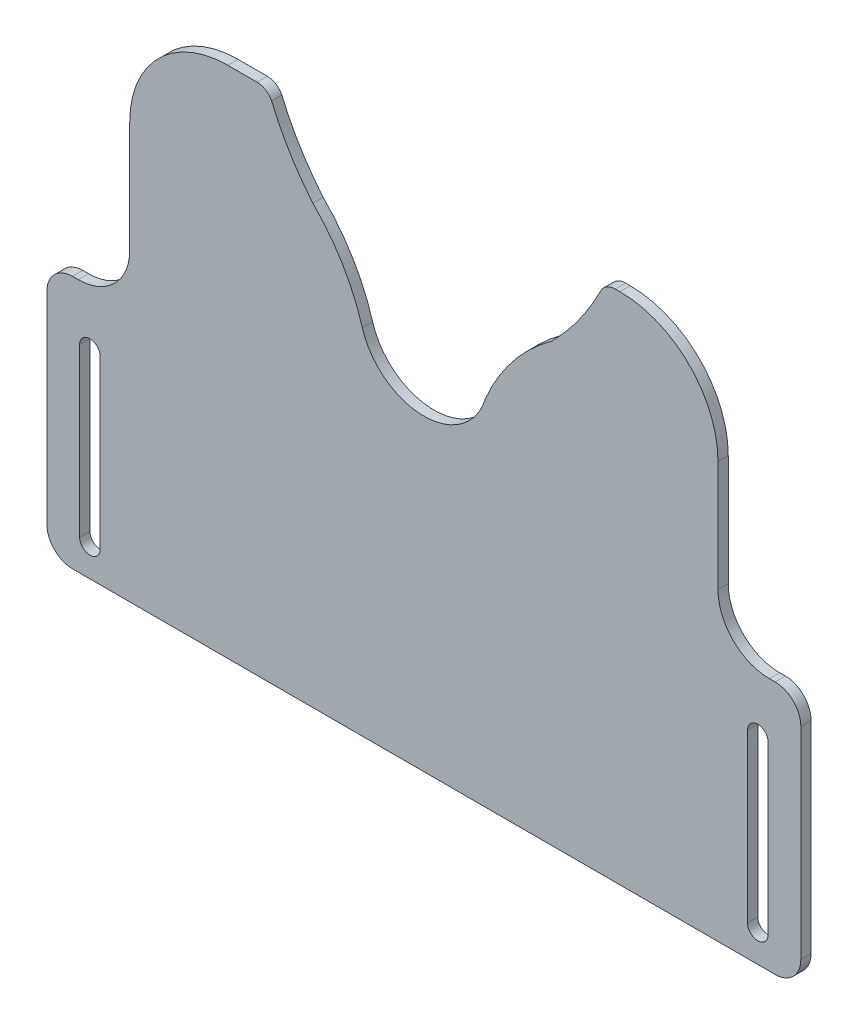
SolidWorks part; units mm, degrees
ref_plane "Front Plane" through (0, 0, 0) normal (0, 0, 1) x (1, 0, 0)
ref_plane "Top Plane" through (0, 0, 0) normal (0, 1, 0) x (1, 0, 0)
ref_plane "Right Plane" through (0, 0, 0) normal (1, 0, 0) x (0, 0, -1)
sketch "Sketch2" plane through (0, 0, 0) normal (0, 0, 1) x (1, 0, 0)
  line B0 (76.3333, 193.3656) -> (74.5053, 193.3656)
  line B1 (-64.9636, 193.3656) -> (-76.3333, 193.3656)
  line B2 (-114.5, 155.1989) -> (-114.5, -6.6344)
  line B3 (114.5, -6.6344) -> (114.5, 155.1989)
  arc B4 (114.5, 155.1989) -> (76.3333, 193.3656) centre (76.3333, 155.1989) ccw
  arc B5 (74.5053, 193.3656) -> (68.8157, 189.8492) centre (74.5053, 187.0044) ccw
  arc B6 (49.7507, 163.3979) -> (68.8157, 189.8492) centre (-22.2171, 235.3657) ccw
  arc B7 (49.7507, 163.3979) -> (23.9676, 131.1316) centre (94.2687, 101.3905) ccw
  arc B8 (-23.9676, 131.1316) -> (23.9676, 131.1316) centre (0, 138.2417) ccw
  arc B9 (-23.9676, 131.1316) -> (-43.1729, 163.3979) centre (-97.1487, 109.4221) ccw
  arc B10 (-59.274, 189.8492) -> (-43.1729, 163.3979) centre (34.7026, 228.9275) ccw
  arc B11 (-59.274, 189.8492) -> (-64.9636, 193.3656) centre (-64.9636, 187.0044) ccw
  arc B12 (-76.3333, 193.3656) -> (-114.5, 155.1989) centre (-76.3333, 155.1989) ccw
  line B13 (-114.5, -6.6344) -> (114.5, -6.6344)
sketch_block_instance "Block1-1"
sketch_block "Block1" parameters "D1"=11.3697, "D2"=229
extrude "Boss-Extrude1" add sketch "Sketch2" along normal blind 4
sketch "Sketch3" plane through (0, 0, 4) normal (0, 0, 1) x (1, 0, 0)
  line L0 (-114.5, -6.6344) -> (-146.7474, -6.6344)
  line L1 (-146.7474, -6.6344) -> (-146.7474, 92)
  line L2 (-146.7474, 92) -> (-114.5, 92)
  line L3 (-114.5, 155.1989) -> (-114.5, -6.6344) construction
  line L4 (-114.5, 92) -> (-114.5, -6.6344)
  line L5 (-130, 70.3656) -> (-130, 5.3656) construction
  line L6 (-126, 70.3656) -> (-126, 5.3656)
  line L7 (-134, 70.3656) -> (-134, 5.3656)
  line L8 (0, -6.6344) -> (0, 127.9164) construction
  line L9 (130, 70.3656) -> (130, 5.3656) construction
  line L10 (126, 70.3656) -> (126, 5.3656)
  line L11 (134, 70.3656) -> (134, 5.3656)
  line L12 (114.5, 92) -> (114.5, -6.6344)
  line L13 (146.7474, 92) -> (114.5, 92)
  line L14 (146.7474, -6.6344) -> (146.7474, 92)
  line L15 (114.5, -6.6344) -> (146.7474, -6.6344)
  line L16 (-114.5, -6.6344) -> (114.5, -6.6344) construction
  arc A0 (-126, 70.3656) -> (-134, 70.3656) centre (-130, 70.3656) ccw
  arc A1 (-134, 5.3656) -> (-126, 5.3656) centre (-130, 5.3656) ccw
  arc A2 (-131.771, 17.4502) -> (-128.229, 17.4502) centre (-130, 20.3526) ccw construction
  arc A3 (-103.5, 5.3656) -> (-95.5, 5.3656) centre (-99.5, 5.3656) ccw construction
  arc A4 (-103.5, 5.3656) -> (-95.5, 5.3656) centre (-99.5, 5.3656) ccw construction
  arc A5 (126, 70.3656) -> (134, 70.3656) centre (130, 70.3656) cw
  arc A6 (134, 5.3656) -> (126, 5.3656) centre (130, 5.3656) cw
  arc A7 (103.5, 5.3656) -> (95.5, 5.3656) centre (99.5, 5.3656) cw construction
  point P10 (-130, 37.8656)
  point P18 (-130, 16.9526)
  point P26 (130, 37.8656)
  dimension "D1" = 4
  dimension "D2" = 65
extrude "Boss-Extrude2" add sketch "Sketch3" against normal blind 4
fillet "Fillet1" radius 10 4 edges at (146.7474, 92, 2) (146.7474, -6.6344, 2) (-146.7474, -6.6344, 2) (-146.7474, 92, 2)
fillet "Fillet2" radius 20 2 edges at (-114.5, 92, 2)
